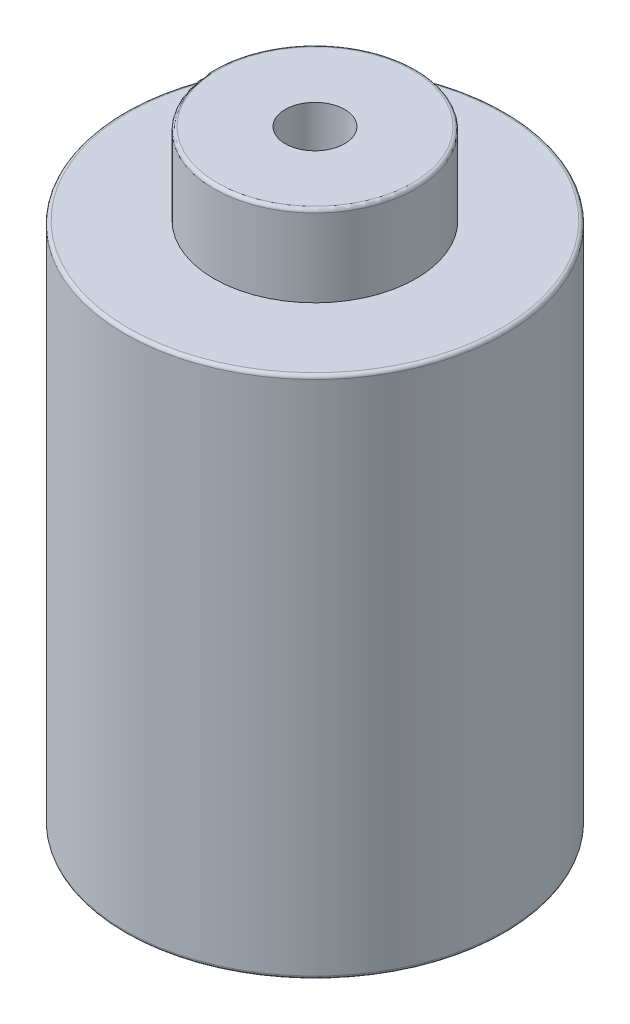
SolidWorks part; units mm, degrees
ref_plane "Front Plane" through (0, 0, 0) normal (0, 0, 1) x (1, 0, 0)
ref_plane "Top Plane" through (0, 0, 0) normal (0, 1, 0) x (1, 0, 0)
ref_plane "Right Plane" through (0, 0, 0) normal (1, 0, 0) x (0, 0, -1)
sketch "Sketch1" plane through (0, 0, 0) normal (0, 1, 0) x (1, 0, 0)
  circle A0 centre (0, 0) radius 13.97
  circle A1 centre (0, 0) radius 2.1844
  dimension "D1" = 27.94
  dimension "D2" = 4.3688
extrude "Boss-Extrude1" add sketch "Sketch1" along normal blind 44.45
sketch "Sketch2" plane through (0, 44.45, 0) normal (0, 1, 0) x (1, 0, 0)
  circle A0 centre (0, 0) radius 7.4295
  circle A1 centre (0, 0) radius 13.97
  circle A2 centre (0, 0) radius 13.97
  dimension "D2" = 14.859
  dimension "D1" = 0
extrude "Cut-Extrude1" cut sketch "Sketch2" against normal blind 5.969
fillet "Fillet1" radius 0.254 3 edges at (0, 0, 13.97) (0, 38.481, 13.97) (0, 44.45, 7.4295)
